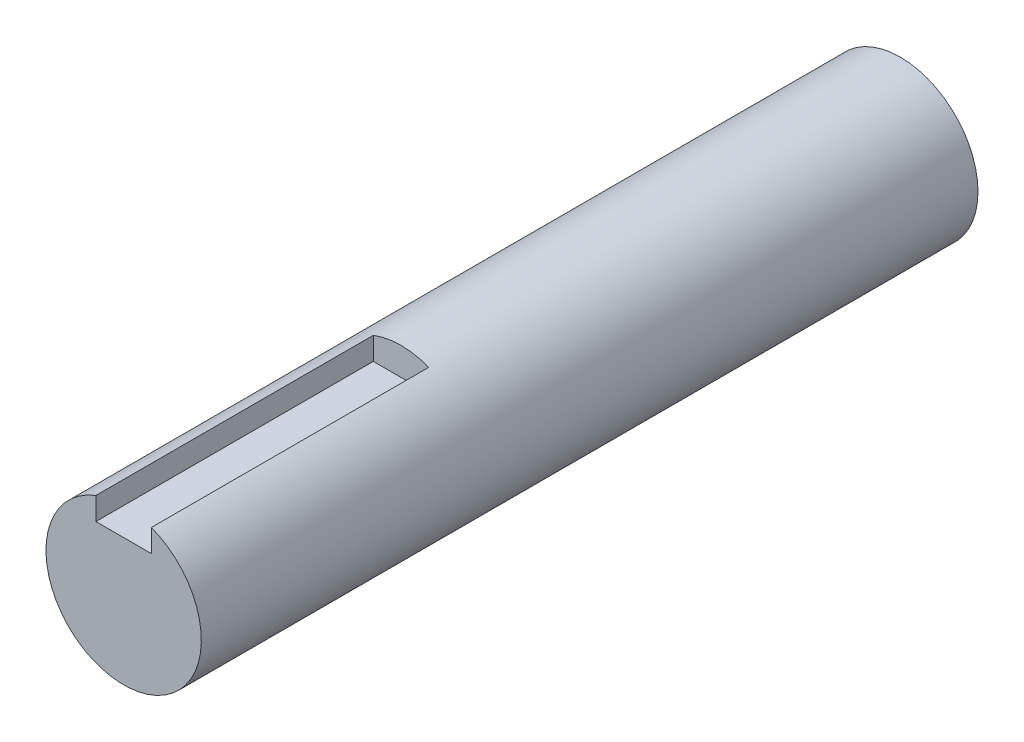
SolidWorks part; units mm, degrees
ref_plane "Front Plane" through (0, 0, 0) normal (0, 0, 1) x (1, 0, 0)
ref_plane "Top Plane" through (0, 0, 0) normal (0, 1, 0) x (1, 0, 0)
ref_plane "Right Plane" through (0, 0, 0) normal (1, 0, 0) x (0, 0, -1)
sketch "Sketch1" plane through (0, 0, 0) normal (0, 0, 1) x (1, 0, 0)
  circle A0 centre (0, 0) radius 7
  dimension "D1" = 14
extrude "Boss-Extrude1" add sketch "Sketch1" along normal blind 70
sketch "Sketch2" plane through (0, 0, 70) normal (0, 0, 1) x (1, 0, 0)
  line L0 (0, 4.5) -> (0, 0) construction
  line L1 (-2.5, 4.5) -> (2.5, 4.5)
  line L2 (-2.5, 4.5) -> (-2.5, 6.5383)
  line L4 (2.5, 4.5) -> (2.5, 6.5383)
  line L5 (-2.5, 4.5) -> (0, 7) construction
  line L6 (0, 7) -> (2.5, 4.5) construction
  circle A0 centre (0, 0) radius 7 construction
  arc A1 (2.5, 6.5383) -> (-2.5, 6.5383) centre (0, 0) ccw
  point P0 (0, 7)
  dimension "D1" = 5
  dimension "D2" = 2.5
extrude "Cut-Extrude1" cut sketch "Sketch2" against normal blind 25
